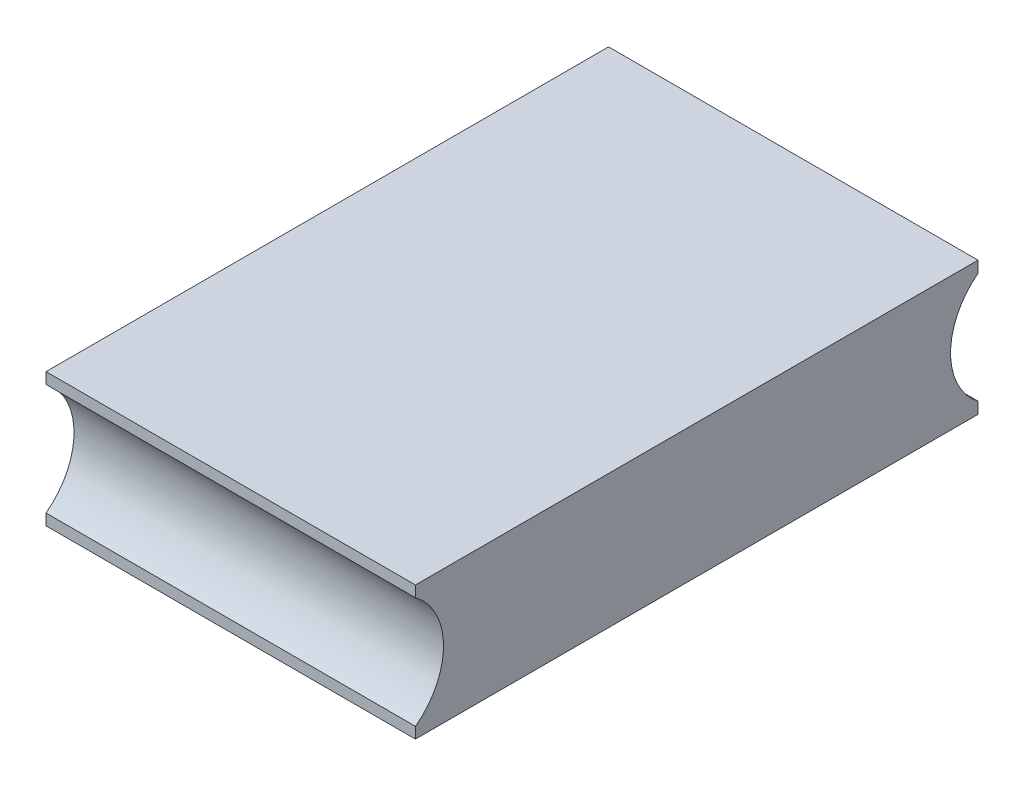
SolidWorks part; units mm, degrees
ref_plane "정면" through (0, 0, 0) normal (0, 0, 1) x (1, 0, 0)
ref_plane "윗면" through (0, 0, 0) normal (0, 1, 0) x (1, 0, 0)
ref_plane "우측면" through (0, 0, 0) normal (1, 0, 0) x (0, 0, -1)
sketch "스케치1" plane through (0, 0, 0) normal (1, 0, 0) x (0, 0, -1)
  line L0 (-69.267, 12.0521) -> (-69.267, 14.4568)
  line L1 (-69.267, 14.4568) -> (52.5408, 14.4568)
  line L2 (0, 14.4568) -> (0, 0) construction
  line L3 (0, 0) -> (-63.1971, 0) construction
  line L6 (-69.267, -14.4568) -> (52.5408, -14.4568)
  line L7 (-69.267, -12.0521) -> (-69.267, -14.4568)
  line L8 (52.5408, 14.4568) -> (52.5408, 11.978)
  line L9 (52.5408, -11.978) -> (52.5408, -14.4568)
  arc A0 (-69.267, -12.0521) -> (-69.267, 12.0521) centre (-78.1971, 0) ccw
  arc A2 (52.5408, 11.978) -> (52.5408, -11.978) centre (61.6405, 0) ccw
  point P9 (0, 0)
  dimension "D1" = 15
extrude "보스-돌출1" add sketch "스케치1" along normal mid plane 80
